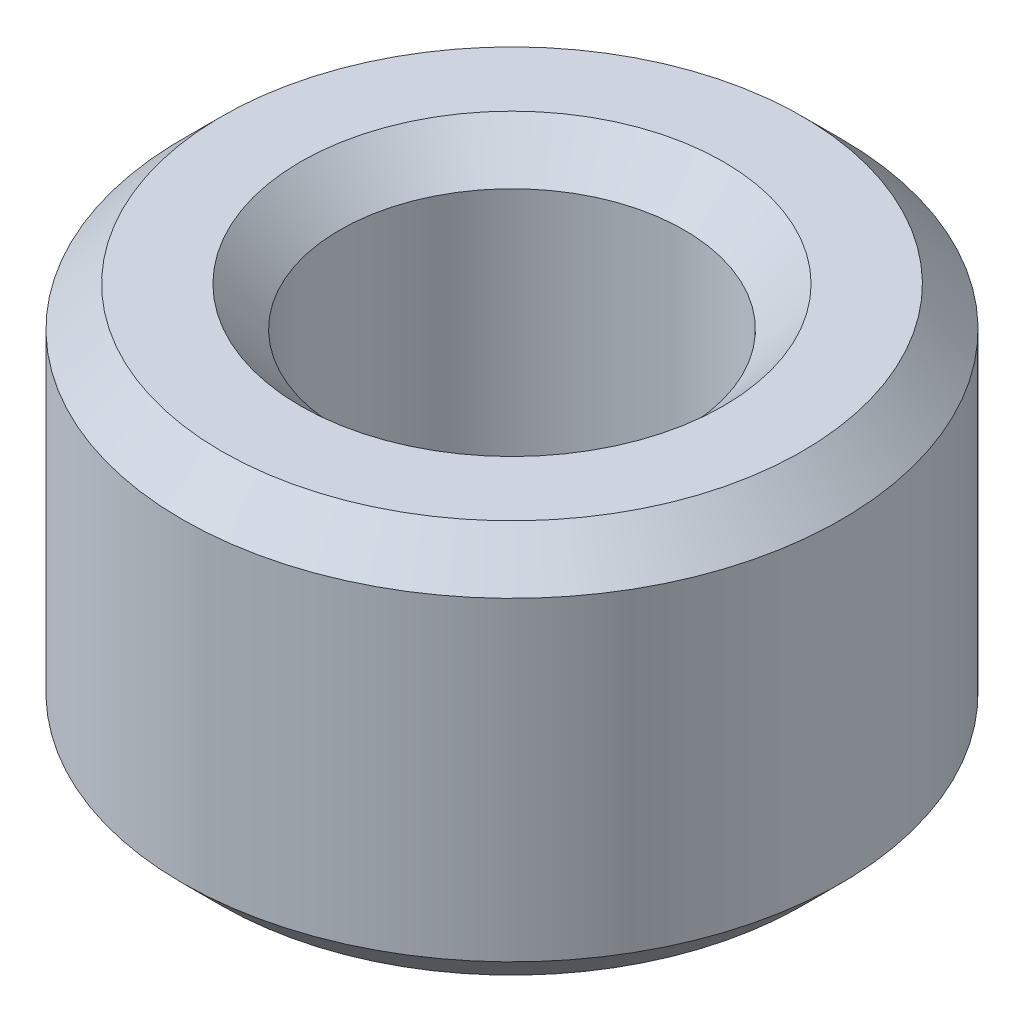
SolidWorks part; units mm, degrees
ref_plane "Front Plane" through (0, 0, 0) normal (0, 0, 1) x (1, 0, 0)
ref_plane "Top Plane" through (0, 0, 0) normal (0, 1, 0) x (1, 0, 0)
ref_plane "Right Plane" through (0, 0, 0) normal (1, 0, 0) x (0, 0, -1)
sketch "Sketch2" plane through (0, 0, 0) normal (0, 1, 0) x (1, 0, 0)
  circle A0 centre (0, 0) radius 1.75
  circle A1 centre (0, 0) radius 3.35
  dimension "D1" = 1.6
  dimension "D2" = 3.5
extrude "Boss-Extrude1" add sketch "Sketch2" along normal blind 4
chamfer "Chamfer1" distance 0.4 angle 45 4 edges at (0, 0, 3.35) (0, 0, 1.75) (0, 4, 3.35) (0, 4, 1.75)
